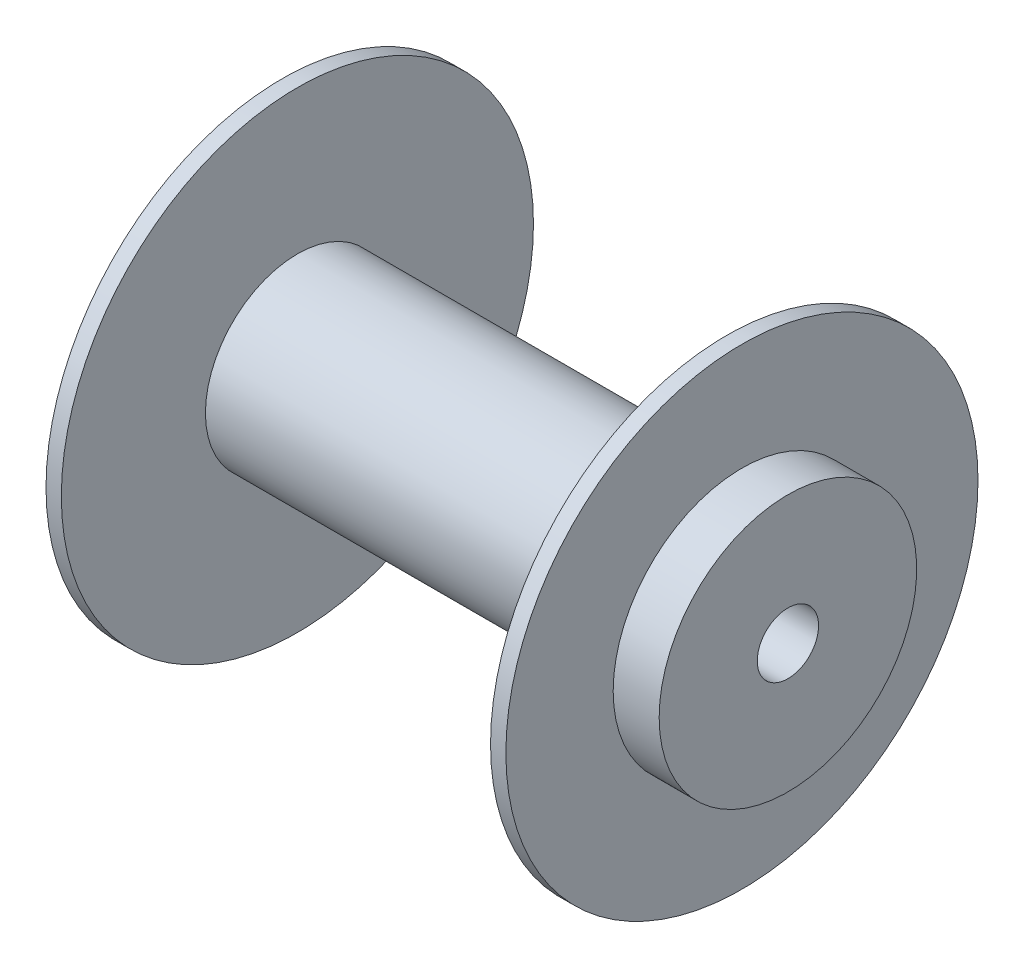
SolidWorks part; units mm, degrees
ref_plane "Plan de face" through (0, 0, 0) normal (0, 0, 1) x (1, 0, 0)
ref_plane "Plan de dessus" through (0, 0, 0) normal (0, 1, 0) x (1, 0, 0)
ref_plane "Plan de droite" through (0, 0, 0) normal (1, 0, 0) x (0, 0, -1)
sketch "Esquisse1" plane through (0, 0, 0) normal (0, 0, 1) x (1, 0, 0)
  line L0 (0, 0) -> (0, 12)
  line L1 (0, 12) -> (15, 12)
  line L2 (15, 12) -> (15, 47)
  line L3 (15, 47) -> (20, 47)
  line L4 (20, 47) -> (20, 0)
  line L6 (160, 0) -> (160, 47)
  line L7 (160, 47) -> (165, 47)
  line L8 (165, 47) -> (165, 12)
  line L9 (165, 12) -> (180, 12)
  line L10 (180, 12) -> (180, 0)
  line L11 (180, 0) -> (160, 0)
  line L12 (0, -30) -> (192.8259, -30) construction
  line L13 (20, 0) -> (0, 0)
  line L15 (0, 0) -> (180, 0)
  line L19 (0, 0) -> (180, 0)
  line L20 (0, 0) -> (0, -20)
  line L21 (0, -20) -> (180, -20)
  line L22 (180, 0) -> (180, -20)
  dimension "D1" = 30
  dimension "D2" = 12
  dimension "D3" = 5
  dimension "D4" = 15
  dimension "D5" = 35
  dimension "D6" = 180
  dimension "D7" = 10
revolve "Révolution1" add sketch "Esquisse1" angle 360 about L12
